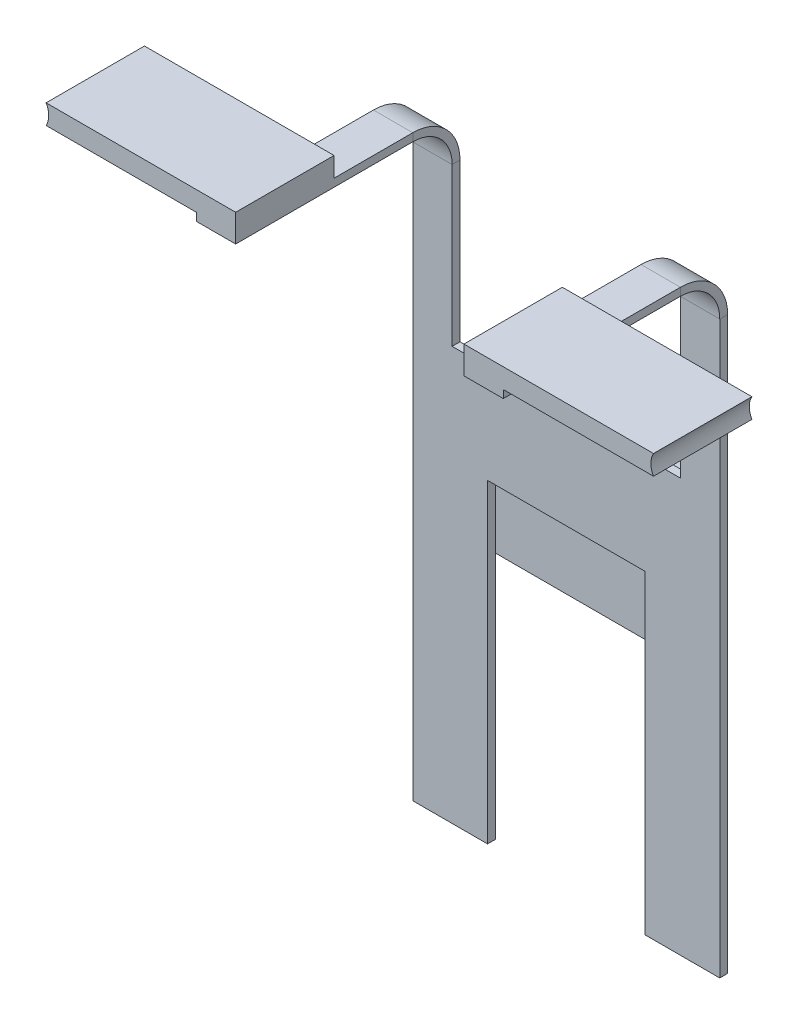
SolidWorks part; units mm, degrees
ref_plane "Front" through (0, 0, 0) normal (0, 0, 1) x (1, 0, 0)
ref_plane "Top" through (0, 0, 0) normal (0, 1, 0) x (1, 0, 0)
ref_plane "Right" through (0, 0, 0) normal (1, 0, 0) x (0, 0, -1)
sketch "草图1" plane through (0, 0, 0) normal (0, 0, 1) x (1, 0, 0)
  line L1 (0, 0) -> (0, -101.6526) construction
  line L2 (-40, 0) -> (40, 0)
  line L4 (-78, 0) -> (-78, 50)
  line L5 (-78, 50) -> (78, 50)
  line L6 (78, 0) -> (78, 50)
  line L8 (-78, 0) -> (-78, -160)
  line L9 (-78, -160) -> (-40, -160)
  line L10 (-40, 0) -> (-40, -160)
  line L12 (78, 0) -> (78, -160)
  line L13 (78, -160) -> (40, -160)
  line L14 (40, 0) -> (40, -160)
  dimension "D1" = 156
  dimension "D2" = 78
  dimension "D3" = 50
  dimension "D4" = 160
  dimension "D5" = 38
  dimension "D6" = 38
extrude "凸台-拉伸1" add sketch "草图1" along normal blind 4
sketch "草图2" plane through (0, 0, 0) normal (0, 0, -1) x (-1, 0, 0)
  line L0 (0, 50) -> (0, -108.7421) construction
  line L1 (-50, 38) -> (50, 38)
  line L2 (-50, 38) -> (-50, -34)
  line L3 (-50, -34) -> (50, -34)
  line L4 (50, 38) -> (50, -34)
  line L5 (-78, 50) -> (78, 50) construction
  line L6 (-78, 50) -> (78, 50) construction
  dimension "D1" = 100
  dimension "D2" = 50
  dimension "D3" = 12
  dimension "D4" = 72
extrude "凸台-拉伸2" add sketch "草图2" along normal blind 20
sketch "草图4" plane through (0, 50, 0) normal (0, 1, 0) x (1, 0, 0)
  line L0 (78, 0) -> (-78, 0) construction
  line L1 (-78, -4) -> (-58, -4)
  line L2 (-78, -4) -> (-78, 0)
  line L3 (-78, 0) -> (-58, 0)
  line L4 (-58, -4) -> (-58, 0)
  line L5 (78, -4) -> (-78, -4) construction
  line L6 (78, 0) -> (58, 0)
  line L7 (78, 0) -> (78, -4)
  line L8 (78, -4) -> (58, -4)
  line L9 (58, 0) -> (58, -4)
  dimension "D1" = 20
  dimension "D2" = 20
sketch "草图5" plane through (-78, 0, 0) normal (-1, 0, 0) x (0, 0, 1)
  line L0 (0, 50) -> (0, 130)
  line L1 (0, 130) -> (-75.9412, 130) construction
  line L3 (0, 130) -> (34.1219, 130) construction
  line L4 (24, 154) -> (114, 154)
  arc A1 (24, 154) -> (0, 130) centre (24, 130) ccw
  point P7 (-24, 154)
  dimension "D2" = 90
sweep "扫描1" add profiles "草图4" path "草图5"
sketch "草图7" plane through (-58, 0, 0) normal (1, 0, 0) x (0, 0, -1)
  line L1 (-114, 154) -> (-64, 154)
  line L2 (-114, 154) -> (-114, 164)
  line L3 (-114, 164) -> (-64, 164)
  line L4 (-64, 154) -> (-64, 164)
  dimension "D1" = 10
  dimension "D2" = 50
sketch "草图8" plane through (0, 0, 114) normal (0, 0, 1) x (1, 0, 0)
  line L0 (-58, 154) -> (-158, 154)
sweep "扫描2" add profiles "草图7" path "草图8"
sketch "草图9" plane through (58, 0, 0) normal (-1, 0, 0) x (0, 0, 1)
  line L1 (64, 164) -> (114, 164)
  line L2 (64, 164) -> (64, 154)
  line L3 (64, 154) -> (114, 154)
  line L4 (114, 164) -> (114, 154)
sketch "草图10" plane through (0, 0, 114) normal (0, 0, 1) x (1, 0, 0)
  line L0 (58, 154) -> (158, 154)
sweep "扫描3" add profiles "草图9" path "草图10"
sketch "草图12" plane through (0, 0, 114) normal (0, 0, 1) x (1, 0, 0)
  line L0 (-158, 159) -> (-180.8497, 159) construction
  line L1 (-158, 164) -> (-158, 154) construction
  line L2 (-158, 184) -> (-158, 122.2922) construction
  line L3 (158, 159) -> (220.5736, 159) construction
  line L4 (158, 154) -> (158, 164) construction
  circle A0 centre (-163, 159) radius 10
  circle A1 centre (163, 159) radius 10
  dimension "D1" = 5
  dimension "D2" = 5
extrude "切除-拉伸1" cut sketch "草图12" against normal through all
